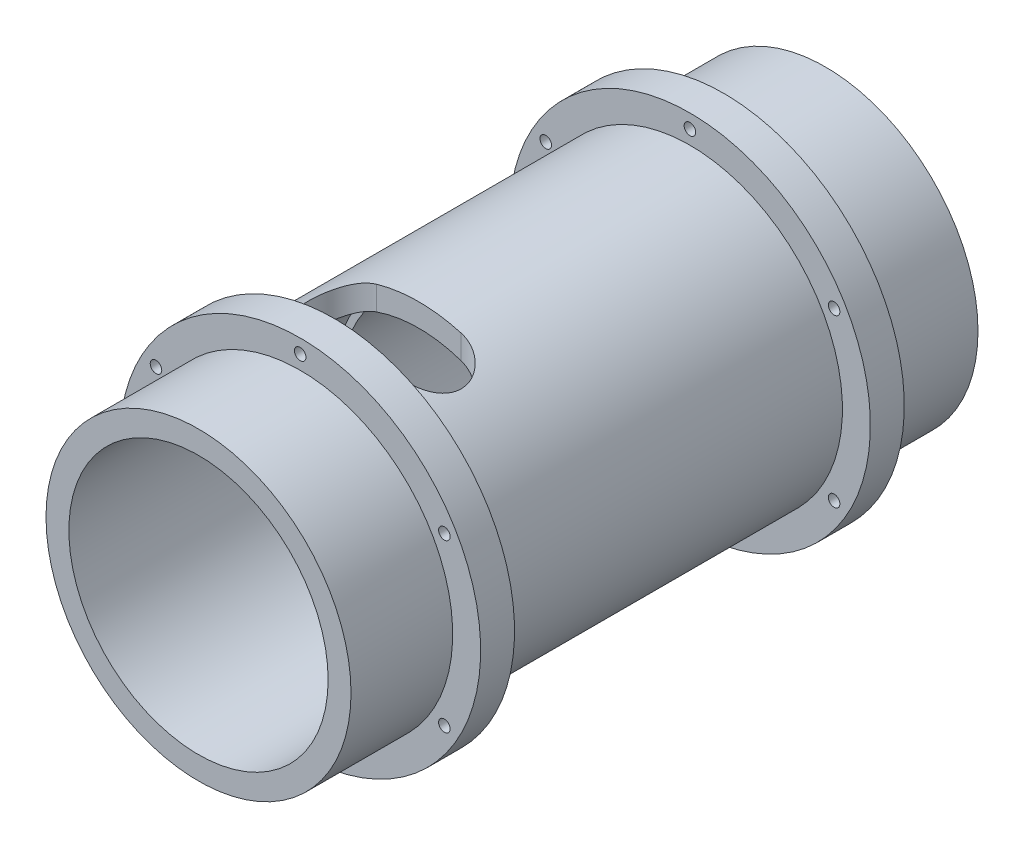
SolidWorks part; units mm, degrees
material "6061-T6 (SS)"
ref_plane "Front Plane" through (0, 0, 0) normal (0, 0, 1) x (1, 0, 0)
ref_plane "Top Plane" through (0, 0, 0) normal (0, 1, 0) x (1, 0, 0)
ref_plane "Right Plane" through (0, 0, 0) normal (1, 0, 0) x (0, 0, -1)
sketch "Sketch1" plane through (0, 0, 0) normal (0, 0, 1) x (1, 0, 0)
  circle A0 centre (0, 0) radius 33.75
  circle A1 centre (0, 0) radius 45
  dimension "D1" = 67.5
  dimension "D2" = 90
extrude "Boss-Extrude1" add sketch "Sketch1" along normal mid plane 185
sketch "Sketch2" plane through (0, 0, 0) normal (0, 1, 0) x (1, 0, 0)
  line L0 (0, -92.5) -> (0, 92.5)
  line L1 (-45, -92.5) -> (45, -92.5) construction
  line L2 (33.75, 92.5) -> (-33.75, 92.5) construction
  line L6 (-38.25, -92.5) -> (-38.25, -13.85)
  line L7 (-38.25, -13.85) -> (-36.25, -13.85)
  line L8 (-36.25, -13.85) -> (-36.25, 86.15)
  line L9 (-36.25, 86.15) -> (-38.25, 86.15)
  line L10 (-38.25, 86.15) -> (-38.25, 92.5)
  line L11 (-38.25, 92.5) -> (0, 92.5)
  line L12 (0, -92.5) -> (-38.25, -92.5)
  dimension "D1" = 78.65
  dimension "D2" = 6.35
  dimension "D3" = 38.25
  dimension "D6" = 36.25
revolve "Cut-Revolve1" cut sketch "Sketch2" angle 360 about L0
sketch "Sketch4" plane through (0, 0, 0) normal (1, 0, 0) x (0, 0, -1)
  line L0 (-62.5, 45) -> (-62.5, 53.25)
  line L1 (92.5, 45) -> (-92.5, 45) construction
  line L2 (-62.5, 53.25) -> (-52.5, 53.25)
  line L3 (-52.5, 53.25) -> (-52.5, 45)
  line L4 (-52.5, 45) -> (-62.5, 45)
  line L5 (-92.5, 45) -> (-92.5, -45) construction
  line L7 (0, 0) -> (0, 45) construction
  line L8 (92.5, 45) -> (-92.5, 45) construction
  line L9 (52.5, 53.25) -> (52.5, 45)
  line L10 (62.5, 53.25) -> (52.5, 53.25)
  line L11 (62.5, 45) -> (62.5, 53.25)
  line L12 (52.5, 45) -> (62.5, 45)
  line L13 (92.5, 0) -> (-92.5, 0) construction
  line L14 (92.5, -45) -> (92.5, 45) construction
  dimension "D1" = 30
  dimension "D2" = 8.25
  dimension "D3" = 10
revolve "Revolve1" add sketch "Sketch4" angle 360 about L13
sketch "Sketch7" plane through (0, 0, 62.5) normal (0, 0, 1) x (1, 0, 0)
  line L0 (0, 45) -> (0, 53.25) construction
  circle A0 centre (0, 0) radius 45 construction
  circle A1 centre (0, 0) radius 53.25 construction
  circle A2 centre (0, 0) radius 49.125 construction
  point P10 (0, 49.125)
  point P23 (0, 49.125)
  point P26 (0, 0)
sketch "Sketch3" plane through (0, 0, 0) normal (0, 1, 0) x (1, 0, 0)
  line L0 (-12.5, -37.5) -> (12.5, -37.5) construction
  line L1 (-12.5, -27.5) -> (12.5, -27.5)
  line L2 (-12.5, -47.5) -> (12.5, -47.5)
  line L5 (-45, -92.5) -> (45, -92.5) construction
  arc A0 (-12.5, -27.5) -> (-12.5, -47.5) centre (-12.5, -37.5) ccw
  arc A1 (12.5, -47.5) -> (12.5, -27.5) centre (12.5, -37.5) ccw
  point P2 (0, -37.5)
  dimension "D3" = 10
  dimension "D1" = 55
  dimension "D2" = 25
extrude "Cut-Extrude1" cut sketch "Sketch3" along normal through all
hole_wizard "M3 Clearance Hole1" positions "Sketch7" profile "Sketch8" hole size "M3" standard "ANSI Metric" end condition through all
sketch "Sketch8" plane through (0, 49.125, 62.5) normal (1, 0, 0) x (0, -1, 0)
  line L0 (0, 0) -> (0, 155)
  line L1 (0, 155) -> (1.7, 155)
  line L2 (1.7, 155) -> (1.7, 0)
  line L5 (1.7, 0) -> (0, 0)
  line L11 (0, -6.35) -> (0, 107.95) construction
  dimension "Thru Hole Dia." = 3.4
  dimension "Thru Hole Depth" = 155
pattern_circular "CirPattern1" count 6 over 360 about axis through (0, 0, 0) along (0, 0, 1) of "M3 Clearance Hole1"
